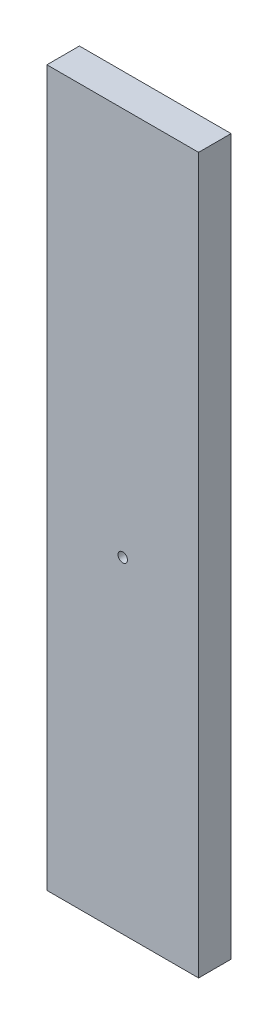
SolidWorks part; units mm, degrees
ref_plane "Front Plane" through (0, 0, 0) normal (0, 0, 1) x (1, 0, 0)
ref_plane "Top Plane" through (0, 0, 0) normal (0, 1, 0) x (1, 0, 0)
ref_plane "Right Plane" through (0, 0, 0) normal (1, 0, 0) x (0, 0, -1)
sketch "Sketch1" plane through (0, 0, 0) normal (0, 1, 0) x (1, 0, 0)
  line L1 (0, 0) -> (88.9, 0)
  line L2 (0, 0) -> (0, 19.05)
  line L3 (0, 19.05) -> (88.9, 19.05)
  line L4 (88.9, 0) -> (88.9, 19.05)
  dimension "D1" = 19.05
  dimension "D2" = 88.9
extrude "Boss-Extrude1" add sketch "Sketch1" along normal blind 419.1
sketch "Sketch2" plane through (0, 0, 0) normal (0, 0, 1) x (1, 0, 0)
  line L0 (44.45, 419.1) -> (44.45, 191.3014) construction
  line L1 (0, 419.1) -> (88.9, 419.1) construction
  line L2 (-349.25, 239.6416) -> (44.45, 191.3014) construction
  line L3 (-349.25, 239.6416) -> (-39.4224, 239.6416) construction
  circle A0 centre (44.45, 191.3014) radius 2.7781
  circle A1 centre (-349.25, 239.6416) radius 2.7781 construction
  circle A2 centre (-349.25, 239.6416) radius 2.7781 construction
  dimension "D1" = 5.5562
  dimension "D2" = 7
extrude "Cut-Extrude1" cut sketch "Sketch2" against normal through all
equation "\"DROPANGLE\"= 10"
